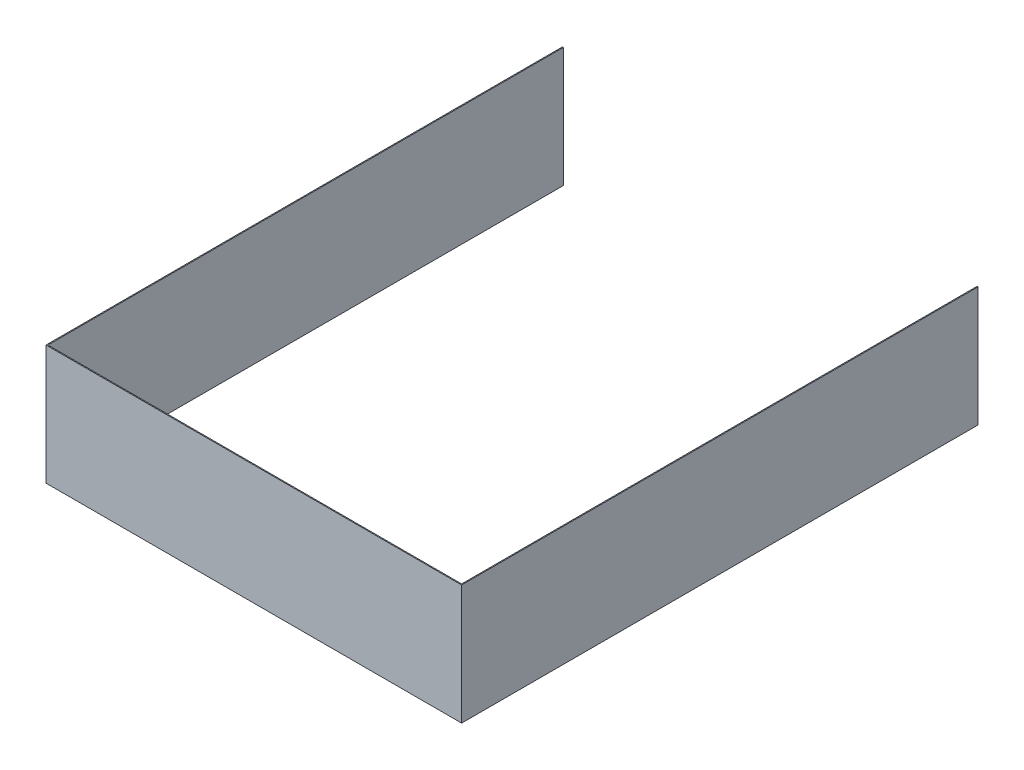
SolidWorks part; units mm, degrees
ref_plane "Front Plane" through (0, 0, 0) normal (0, 0, 1) x (1, 0, 0)
ref_plane "Top Plane" through (0, 0, 0) normal (0, 1, 0) x (1, 0, 0)
ref_plane "Right Plane" through (0, 0, 0) normal (1, 0, 0) x (0, 0, -1)
other "Configuration Table"
sketch "Sketch1" plane through (0, 0, 0) normal (0, 1, 0) x (1, 0, 0)
  line L0 (20, 800) -> (20, -20)
  line L1 (20, -20) -> (680, -20)
  line L2 (680, -20) -> (680, 800)
  line L3 (680, 800) -> (678.5, 800)
  line L4 (678.5, 800) -> (678.5, -18.5)
  line L5 (678.5, -18.5) -> (21.5, -18.5)
  line L6 (21.5, -18.5) -> (21.5, 800)
  line L7 (21.5, 800) -> (20, 800)
extrude "TOPPING_plint_U_1" add sketch "Sketch1" along normal blind 190 from offset 10 separate body
